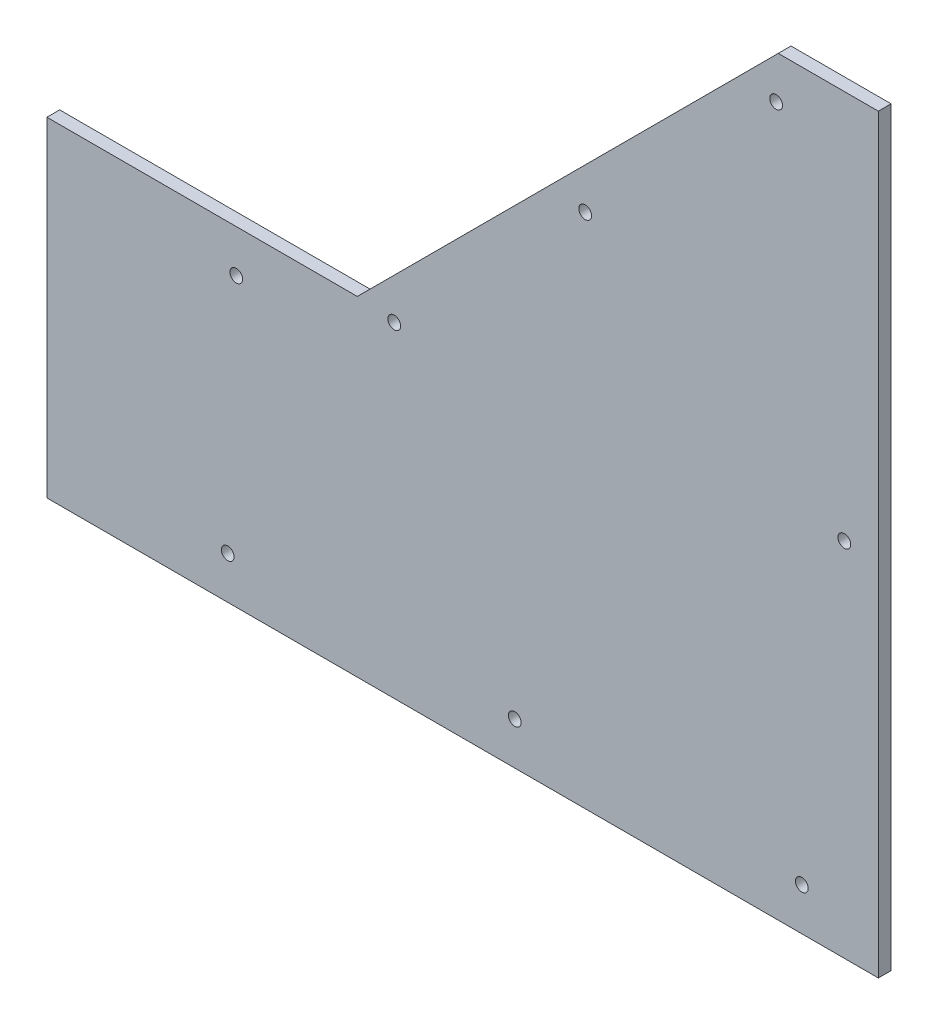
SolidWorks part; units mm, degrees
ref_plane "Front Plane" through (0, 0, 0) normal (0, 0, 1) x (1, 0, 0)
ref_plane "Top Plane" through (0, 0, 0) normal (0, 1, 0) x (1, 0, 0)
ref_plane "Right Plane" through (0, 0, 0) normal (1, 0, 0) x (0, 0, -1)
sketch "Sketch1" plane through (0, 0, 0) normal (0, 0, 1) x (1, 0, 0)
  line L0 (0, 0) -> (-195.53, 0)
  line L1 (0, 0) -> (0, 176.54)
  line L2 (0, 176.54) -> (-23.54, 176.54)
  line L3 (-23.54, 176.54) -> (-122.53, 77.54)
  line L4 (-122.53, 77.54) -> (-195.53, 77.54)
  line L5 (-195.53, 77.54) -> (-195.53, 0)
  dimension "D1" = 195.53
  dimension "D2" = 176.54
  dimension "D3" = 23.54
  dimension "D4" = 73
  dimension "D5" = 77.54
extrude "Boss-Extrude1" add sketch "Sketch1" along normal blind 3
sketch "Sketch2" plane through (0, 0, 3) normal (0, 0, 1) x (1, 0, 0)
  line L1 (-23.54, 162.4) -> (-23.54, 176.54) construction
  line L2 (-23.54, 176.54) -> (-122.53, 77.54) construction
  line L3 (-23.54, 162.4) -> (-37.6786, 162.4) construction
  circle A1 centre (-24.04, 166.4) radius 1.5
  dimension "D1" = 3
  dimension "D2" = 14.14
  dimension "D3" = 0.5
  dimension "D4" = 4
extrude "Cut-Extrude1" cut sketch "Sketch2" against normal up to next
pattern_linear "LPattern2" count 3 spacing 63.5 along (-0.7071, -0.7071, 0) of "Cut-Extrude1"
sketch "Sketch3" plane through (0, 0, 3) normal (0, 0, 1) x (1, 0, 0)
  line L0 (0, 0) -> (0, 176.54) construction
  line L1 (-195.53, 0) -> (0, 0) construction
  circle A0 centre (-18, 10) radius 1.5
  circle A1 centre (-85.5, 10) radius 1.5
  circle A2 centre (-153, 10) radius 1.5
  point P10 (0, 0)
  dimension "D2" = 3
  dimension "D4" = 3
  dimension "D5" = 3
  dimension "D1" = 18
  dimension "D3" = 10
  dimension "D6" = 67.5
  dimension "D7" = 67.5
extrude "Cut-Extrude2" cut sketch "Sketch3" against normal up to next
sketch "Sketch4" plane through (0, 0, 3) normal (0, 0, 1) x (1, 0, 0)
  line L0 (-122.53, 77.54) -> (-195.53, 77.54) construction
  circle A0 centre (-150.995, 67.54) radius 1.5
  dimension "D1" = 3
  dimension "D2" = 10
  dimension "D3" = 28.465
extrude "Cut-Extrude3" cut sketch "Sketch4" against normal up to next
sketch "Sketch5" plane through (0, 0, 3) normal (0, 0, 1) x (1, 0, 0)
  line L0 (0, 0) -> (0, 176.54) construction
  line L1 (0, 176.54) -> (-23.54, 176.54) construction
  circle A0 centre (-8, 85.01) radius 1.5
  dimension "D1" = 3
  dimension "D2" = 8
  dimension "D3" = 91.53
extrude "Cut-Extrude4" cut sketch "Sketch5" against normal up to next
